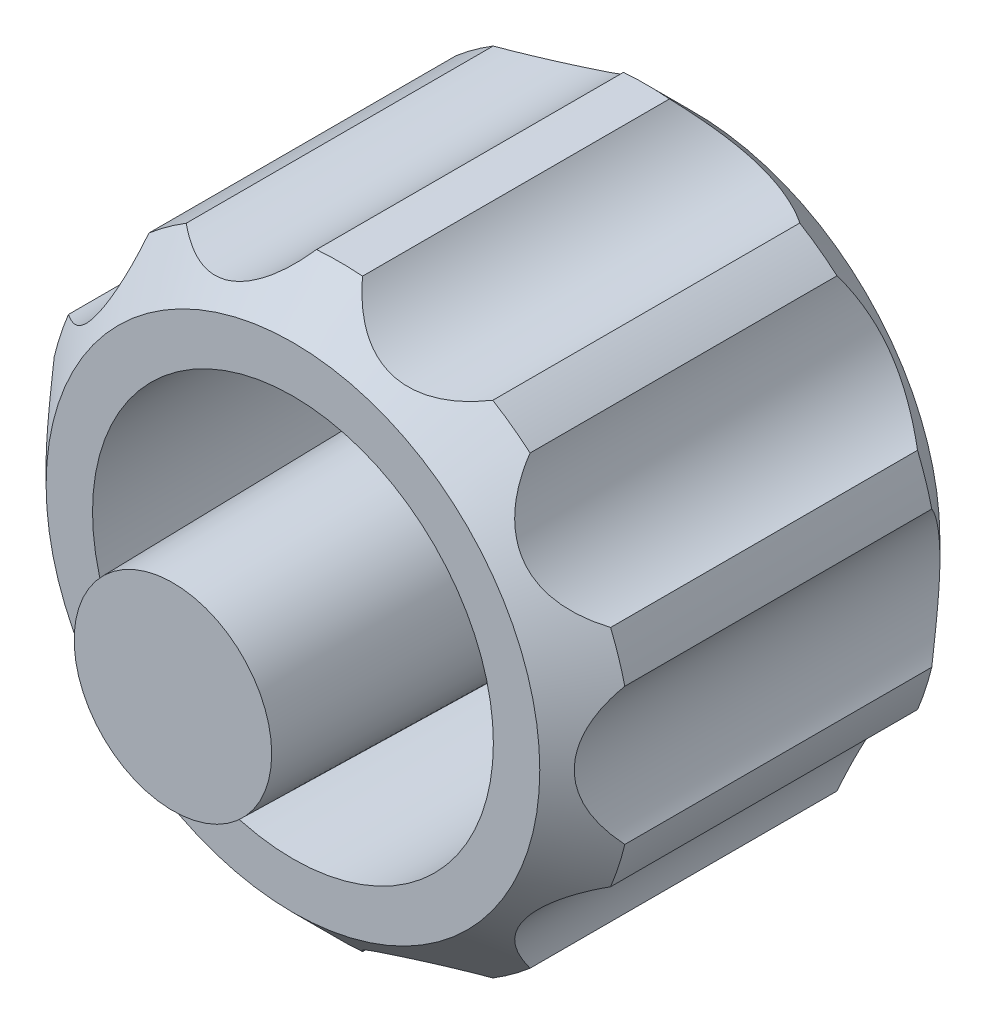
SolidWorks part; units mm, degrees
ref_plane "Front Plane" through (0, 0, 0) normal (0, 0, 1) x (1, 0, 0)
ref_plane "Top Plane" through (0, 0, 0) normal (0, 1, 0) x (1, 0, 0)
ref_plane "Right Plane" through (0, 0, 0) normal (1, 0, 0) x (0, 0, -1)
sketch "Sketch20" plane through (0, 0, 0) normal (0, 0, 1) x (1, 0, 0)
  circle A0 centre (0, 0) radius 3.8171
  arc A1 (-2.9197, 4.7646) -> (-0.4384, 5.5708) centre (-2.2668, 6.9763) ccw
  arc A2 (-2.9197, 4.7646) -> (-3.6291, 4.2491) centre (0, 0) ccw
  arc A3 (-5.1626, 2.1384) -> (-3.6291, 4.2491) centre (-5.9344, 4.3116) ccw
  arc A4 (-5.1626, 2.1384) -> (-5.4336, 1.3045) centre (0, 0) ccw
  arc A5 (-5.4336, -1.3045) -> (-5.4336, 1.3045) centre (-7.3354, 0) ccw
  arc A6 (-5.4336, -1.3045) -> (-5.1626, -2.1384) centre (0, 0) ccw
  arc A7 (-3.6291, -4.2491) -> (-5.1626, -2.1384) centre (-5.9344, -4.3116) ccw
  arc A8 (-3.6291, -4.2491) -> (-2.9197, -4.7646) centre (0, 0) ccw
  arc A9 (-0.4384, -5.5708) -> (-2.9197, -4.7646) centre (-2.2668, -6.9763) ccw
  arc A10 (-0.4384, -5.5708) -> (0.4384, -5.5708) centre (0, 0) ccw
  arc A11 (2.9197, -4.7646) -> (0.4384, -5.5708) centre (2.2668, -6.9763) ccw
  arc A12 (2.9197, -4.7646) -> (3.6291, -4.2491) centre (0, 0) ccw
  arc A13 (5.1626, -2.1384) -> (3.6291, -4.2491) centre (5.9344, -4.3116) ccw
  arc A14 (5.1626, -2.1384) -> (5.4336, -1.3045) centre (0, 0) ccw
  arc A15 (5.4336, 1.3045) -> (5.4336, -1.3045) centre (7.3354, 0) ccw
  arc A16 (5.4336, 1.3045) -> (5.1626, 2.1384) centre (0, 0) ccw
  arc A17 (3.6291, 4.2491) -> (5.1626, 2.1384) centre (5.9344, 4.3116) ccw
  arc A18 (3.6291, 4.2491) -> (2.9197, 4.7646) centre (0, 0) ccw
  arc A19 (0.4384, 5.5708) -> (2.9197, 4.7646) centre (2.2668, 6.9763) ccw
  arc A20 (0.4384, 5.5708) -> (-0.4384, 5.5708) centre (0, 0) ccw
  circle A21 centre (0, 0) radius 5.588 construction
  dimension "D1" = 7.6341
  dimension "D2" = 11.176
extrude "Boss-Extrude1" add sketch "Sketch20" along normal mid plane 7.62
sketch "Sketch21" plane through (0, 0, -3.81) normal (0, 0, -1) x (-1, 0, 0)
  arc A20 (3.6291, 4.2491) -> (2.9197, 4.7646) centre (0, 0) ccw
  arc A21 (0.4384, 5.5708) -> (2.9197, 4.7646) centre (2.2668, 6.9763) ccw
  arc A22 (0.4384, 5.5708) -> (-0.4384, 5.5708) centre (0, 0) ccw
  arc A23 (-2.9197, 4.7646) -> (-0.4384, 5.5708) centre (-2.2668, 6.9763) ccw
  arc A24 (-2.9197, 4.7646) -> (-3.6291, 4.2491) centre (0, 0) ccw
  arc A25 (-5.1626, 2.1384) -> (-3.6291, 4.2491) centre (-5.9344, 4.3116) ccw
  arc A26 (-5.1626, 2.1384) -> (-5.4336, 1.3045) centre (0, 0) ccw
  arc A27 (-5.4336, -1.3045) -> (-5.4336, 1.3045) centre (-7.3354, 0) ccw
  arc A28 (-5.4336, -1.3045) -> (-5.1626, -2.1384) centre (0, 0) ccw
  arc A29 (-3.6291, -4.2491) -> (-5.1626, -2.1384) centre (-5.9344, -4.3116) ccw
  arc A30 (-3.6291, -4.2491) -> (-2.9197, -4.7646) centre (0, 0) ccw
  arc A31 (-0.4384, -5.5708) -> (-2.9197, -4.7646) centre (-2.2668, -6.9763) ccw
  arc A32 (-0.4384, -5.5708) -> (0.4384, -5.5708) centre (0, 0) ccw
  arc A33 (2.9197, -4.7646) -> (0.4384, -5.5708) centre (2.2668, -6.9763) ccw
  arc A34 (2.9197, -4.7646) -> (3.6291, -4.2491) centre (0, 0) ccw
  arc A35 (5.1626, -2.1384) -> (3.6291, -4.2491) centre (5.9344, -4.3116) ccw
  arc A36 (5.1626, -2.1384) -> (5.4336, -1.3045) centre (0, 0) ccw
  arc A37 (5.4336, 1.3045) -> (5.4336, -1.3045) centre (7.3354, 0) ccw
  arc A38 (5.4336, 1.3045) -> (5.1626, 2.1384) centre (0, 0) ccw
  arc A39 (3.6291, 4.2491) -> (5.1626, 2.1384) centre (5.9344, 4.3116) ccw
  arc A40 (3.6291, 4.2491) -> (2.9197, 4.7646) centre (0, 0) ccw
  arc A41 (0.4384, 5.5708) -> (2.9197, 4.7646) centre (2.2668, 6.9763) ccw
  arc A42 (0.4384, 5.5708) -> (-0.4384, 5.5708) centre (0, 0) ccw
  arc A43 (-2.9197, 4.7646) -> (-0.4384, 5.5708) centre (-2.2668, 6.9763) ccw
  arc A44 (-2.9197, 4.7646) -> (-3.6291, 4.2491) centre (0, 0) ccw
  arc A45 (-5.1626, 2.1384) -> (-3.6291, 4.2491) centre (-5.9344, 4.3116) ccw
  arc A46 (-5.1626, 2.1384) -> (-5.4336, 1.3045) centre (0, 0) ccw
  arc A47 (-5.4336, -1.3045) -> (-5.4336, 1.3045) centre (-7.3354, 0) ccw
  arc A48 (-5.4336, -1.3045) -> (-5.1626, -2.1384) centre (0, 0) ccw
  arc A49 (-3.6291, -4.2491) -> (-5.1626, -2.1384) centre (-5.9344, -4.3116) ccw
  arc A50 (-3.6291, -4.2491) -> (-2.9197, -4.7646) centre (0, 0) ccw
  arc A51 (-0.4384, -5.5708) -> (-2.9197, -4.7646) centre (-2.2668, -6.9763) ccw
  arc A52 (-0.4384, -5.5708) -> (0.4384, -5.5708) centre (0, 0) ccw
  arc A53 (2.9197, -4.7646) -> (0.4384, -5.5708) centre (2.2668, -6.9763) ccw
  arc A54 (2.9197, -4.7646) -> (3.6291, -4.2491) centre (0, 0) ccw
  arc A55 (5.1626, -2.1384) -> (3.6291, -4.2491) centre (5.9344, -4.3116) ccw
  arc A56 (5.1626, -2.1384) -> (5.4336, -1.3045) centre (0, 0) ccw
  arc A57 (5.4336, 1.3045) -> (5.4336, -1.3045) centre (7.3354, 0) ccw
  arc A58 (5.4336, 1.3045) -> (5.1626, 2.1384) centre (0, 0) ccw
  arc A59 (3.6291, 4.2491) -> (5.1626, 2.1384) centre (5.9344, 4.3116) ccw
  dimension "D1" = 0
extrude "Boss-Extrude2" add sketch "Sketch21" against normal blind 1.27
sketch "Sketch23" plane through (0, 0, -2.54) normal (0, 0, 1) x (1, 0, 0)
  circle A0 centre (0, 0) radius 2.032
  dimension "D1" = 4.064
extrude "Boss-Extrude3" add sketch "Sketch23" along normal blind 8.636 draft 1
ref_plane "Plane1" through (0, 0, 5.334) normal (0, 0, 1) x (1, 0, 0)
sketch "Sketch24" plane through (0, 0, -3.81) normal (0, 0, 1) x (1, 0, 0)
  circle A0 centre (0, 0) radius 1.143
  dimension "D1" = 2.286
extrude "Cut-Extrude1" cut sketch "Sketch24" along normal up to surface (9.144 mm away)
sketch "Sketch25" plane through (0, 0, 0) normal (1, 0, 0) x (0, 0, -1)
  line L0 (2.9231, 5.588) -> (3.81, 4.7011)
  line L1 (3.81, 5.588) -> (-3.81, 5.588) construction
  line L2 (3.81, 2.1384) -> (3.81, 4.2491) construction
  line L3 (3.81, 4.7011) -> (3.81, 5.588)
  line L5 (3.81, 5.588) -> (2.9231, 5.588)
  line L6 (0, 5.5708) -> (0, 0) construction
  line L7 (-3.81, 5.5708) -> (3.81, 5.5708) construction
  line L8 (-3.81, 5.588) -> (-2.9231, 5.588)
  line L9 (-3.81, 4.7011) -> (-3.81, 5.588)
  line L10 (-2.9231, 5.588) -> (-3.81, 4.7011)
  line L11 (0, 0) -> (3.81, 0) construction
  line L12 (3.81, -1.3045) -> (3.81, 1.3045) construction
  dimension "D1" = 45
  dimension "D2" = 0.0635
revolve "Cut-Revolve1" cut sketch "Sketch25" angle 360 mid plane about L11
fillet "Fillet1" radius 1.016 1 edges at (1.143, 0, -3.81)
